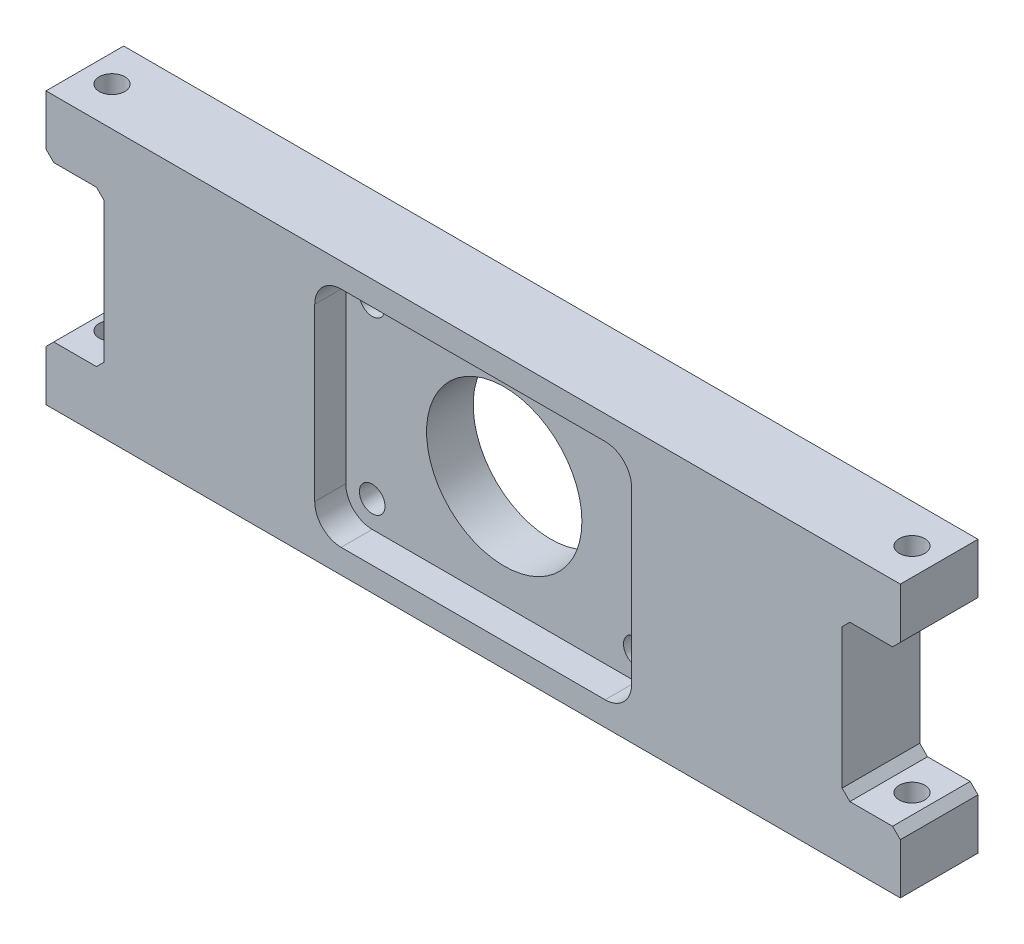
SolidWorks part; units mm, degrees
ref_plane "前视基准面" through (0, 0, 0) normal (0, 0, 1) x (1, 0, 0)
ref_plane "上视基准面" through (0, 0, 0) normal (0, 1, 0) x (1, 0, 0)
ref_plane "右视基准面" through (0, 0, 0) normal (1, 0, 0) x (0, 0, -1)
sketch "草图1" plane through (0, 0, 0) normal (0, 0, 1) x (1, 0, 0)
  line L1 (55, -17.5) -> (-55, -17.5)
  line L2 (55, -17.5) -> (55, 17.5)
  line L3 (55, 17.5) -> (-55, 17.5)
  line L4 (-55, -17.5) -> (-55, 17.5)
  line L5 (55, -17.5) -> (-55, 17.5) construction
  line L6 (55, 17.5) -> (-55, -17.5) construction
  line L7 (17, -11) -> (-17, -11) construction
  line L8 (17, -11) -> (17, 11) construction
  line L9 (17, 11) -> (-17, 11) construction
  line L10 (-17, -11) -> (-17, 11) construction
  line L11 (17, -11) -> (-17, 11) construction
  line L12 (17, 11) -> (-17, -11) construction
  circle A0 centre (-17, 11) radius 1.65
  circle A1 centre (17, 11) radius 1.65
  circle A2 centre (17, -11) radius 1.65
  circle A3 centre (-17, -11) radius 1.65
  point P0 (0, 0)
  point P5 (0, 0)
  dimension "D3" = 3.3
  dimension "D4" = 3.3
  dimension "D5" = 3.3
  dimension "D6" = 3.3
  dimension "D1" = 22
  dimension "D2" = 34
  dimension "D7" = 35
  dimension "D8" = 110
extrude "凸台-拉伸1" add sketch "草图1" along normal blind 10
sketch "草图3" plane through (0, 0, 10) normal (0, 0, 1) x (1, 0, 0)
  line L1 (20, -14) -> (-20, -14)
  line L2 (20, -14) -> (20, 14)
  line L3 (20, 14) -> (-20, 14)
  line L4 (-20, -14) -> (-20, 14)
  line L5 (20, -14) -> (-20, 14) construction
  line L6 (20, 14) -> (-20, -14) construction
  point P0 (0, 0)
  dimension "D1" = 28
  dimension "D2" = 40
extrude "切除-拉伸1" cut sketch "草图3" against normal blind 4
fillet "圆角1" radius 3 4 edges at (20, -14, 8) (20, 14, 8) (-20, -14, 8) (-20, 14, 8)
sketch "草图4" plane through (0, -17.5, 0) normal (0, -1, 0) x (1, 0, 0)
  line L0 (-55, 10) -> (-55, 0) construction
  line L1 (-55, 10) -> (55, 10) construction
  line L2 (0, 0) -> (0, 25.8746) construction
  circle A0 centre (-51.5, 5) radius 1.65
  circle A1 centre (51.5, 5) radius 1.65
  dimension "D1" = 3.3
  dimension "D2" = 3.5
  dimension "D3" = 5
extrude "切除-拉伸2" cut sketch "草图4" against normal through all
sketch "草图5" plane through (0, 0, 6) normal (0, 0, 1) x (1, 0, 0)
  line L0 (-17, -14.4) -> (17, -14.4)
  line L1 (20.4, -11) -> (20.4, 11)
  line L2 (17, 14.4) -> (-17, 14.4)
  line L3 (-20.4, 11) -> (-20.4, -11)
  arc A0 (17, -14.4) -> (20.4, -11) centre (17, -11) ccw
  arc A1 (20.4, 11) -> (17, 14.4) centre (17, 11) ccw
  arc A2 (-17, 14.4) -> (-20.4, 11) centre (-17, 11) ccw
  arc A3 (-20.4, -11) -> (-17, -14.4) centre (-17, -11) ccw
extrude "切除-拉伸3" cut sketch "草图5" along normal up to surface (4 mm away) contours L0 A0 L1 A1 L2 A2 L3 A3 up to face at (0, 0, 10)
sketch "草图7" plane through (0, 0, 0) normal (0, 0, -1) x (-1, 0, 0)
  line L0 (-55, -17.5) -> (-55, 17.5) construction
  line L1 (-62.5, -10) -> (-47.5, -10)
  line L2 (-62.5, -10) -> (-62.5, 10)
  line L3 (-62.5, 10) -> (-47.5, 10)
  line L4 (-47.5, -10) -> (-47.5, 10)
  line L5 (-62.5, -10) -> (-47.5, 10) construction
  line L6 (-62.5, 10) -> (-47.5, -10) construction
  line L7 (55, 17.5) -> (55, -17.5) construction
  line L8 (62.5, -10) -> (47.5, -10)
  line L9 (62.5, -10) -> (62.5, 10)
  line L10 (62.5, 10) -> (47.5, 10)
  line L11 (47.5, -10) -> (47.5, 10)
  line L12 (62.5, -10) -> (47.5, 10) construction
  line L13 (62.5, 10) -> (47.5, -10) construction
  point P0 (-55, 0)
  point P7 (55, 0)
  dimension "D1" = 20
  dimension "D2" = 20
  dimension "D3" = 15
  dimension "D4" = 15
extrude "切除-拉伸5" cut sketch "草图7" against normal through all
chamfer "倒角1" distance 1 angle 45 8 edges at (55, -10, 5) (47.5, -10, 5) (55, 10, 5) (47.5, 10, 5) (-47.5, 10, 5) (-47.5, -10, 5) (-55, -10, 5) (-55, 10, 5)
sketch "草图8" plane through (0, 0, 6) normal (0, 0, 1) x (1, 0, 0)
  circle A0 centre (0, 0) radius 10
  dimension "D1" = 20
extrude "切除-拉伸6" cut sketch "草图8" against normal blind 10
